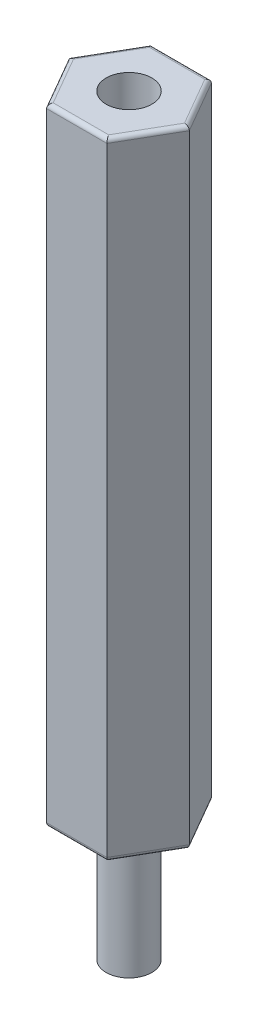
SolidWorks part; units mm, degrees
material "201.0-T43 Molde de fundição com isolamento (SS)"
ref_plane "Plano frontal" through (0, 0, 0) normal (0, 0, 1) x (1, 0, 0)
ref_plane "Plano superior" through (0, 0, 0) normal (0, 1, 0) x (1, 0, 0)
ref_plane "Plano direito" through (0, 0, 0) normal (1, 0, 0) x (0, 0, -1)
sketch "Esboço1" plane through (0, 0, 0) normal (0, 1, 0) x (1, 0, 0)
  line L1 (2.8868, 0) -> (1.4434, 2.5)
  line L2 (1.4434, 2.5) -> (-1.4434, 2.5)
  line L3 (-1.4434, 2.5) -> (-2.8868, 0)
  line L4 (-2.8868, 0) -> (-1.4434, -2.5)
  line L5 (-1.4434, -2.5) -> (1.4434, -2.5)
  line L6 (1.4434, -2.5) -> (2.8868, 0)
  circle A0 centre (0, 0) radius 2.5 construction
  dimension "D1" = 5
extrude "Ressalto-extrusão1" add sketch "Esboço1" along normal blind 30
fillet "Filete1" radius 0.2 12 edges at (0, 30, -2.5) (-2.1651, 30, -1.25) (-2.1651, 30, 1.25) (0, 30, 2.5) (2.1651, 30, 1.25) (2.1651, 30, -1.25) (0, 0, 2.5) (-2.1651, 0, 1.25) (-2.1651, 0, -1.25) (0, 0, -2.5) (2.1651, 0, -1.25) (2.1651, 0, 1.25)
sketch "Esboço2" plane through (0, 0, 0) normal (0, -1, 0) x (1, 0, 0)
  circle A0 centre (0, 0) radius 1.0922
  dimension "D1" = 2.1844
extrude "Ressalto-extrusão2" add sketch "Esboço2" along normal blind 6
sketch "Esboço3" plane through (0, 30, 0) normal (0, 1, 0) x (1, 0, 0)
  circle A0 centre (0, 0) radius 1.0922
extrude "Corte-extrusão1" cut sketch "Esboço3" against normal blind 4.76
